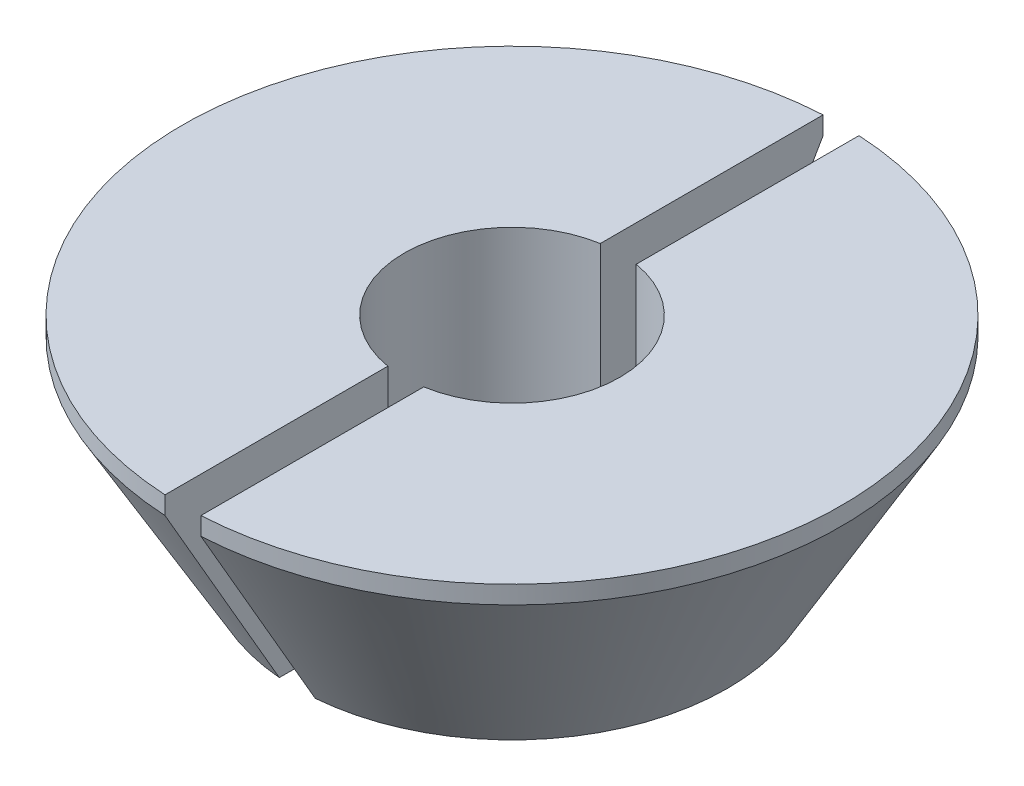
SolidWorks part; units mm, degrees
ref_plane "Front Plane" through (0, 0, 0) normal (0, 0, 1) x (1, 0, 0)
ref_plane "Top Plane" through (0, 0, 0) normal (0, 1, 0) x (1, 0, 0)
ref_plane "Right Plane" through (0, 0, 0) normal (1, 0, 0) x (0, 0, -1)
sketch "Sketch1" plane through (0, 0, 0) normal (0, 0, 1) x (1, 0, 0)
  line L0 (0, 0) -> (3, 0) construction
  line L1 (0, 0) -> (0, 0.0737) construction
  line L2 (0, 0) -> (0, 0.6512) construction
  line L3 (3, 0) -> (4.5877, 2.75)
  line L4 (4.5877, 2.75) -> (4.5877, 3)
  line L5 (4.5877, 3) -> (1.5, 3)
  line L6 (1.5, 3) -> (1.5, 0)
  line L7 (1.5, 0) -> (3, 0)
  dimension "D1" = 0.25
  dimension "D2" = 1.5
  dimension "D3" = 3
  dimension "D4" = 1.5
  dimension "D5" = 60
revolve "Revolve1" add sketch "Sketch1" angle 360 about L2
sketch "Sketch2" plane through (0, 0, 0) normal (0, 0, 1) x (1, 0, 0)
  line L0 (4.5877, 3) -> (-4.5877, 3) construction
  line L1 (0.25, -3) -> (-0.25, -3)
  line L2 (0.25, -3) -> (0.25, 3)
  line L3 (0.25, 3) -> (-0.25, 3)
  line L4 (-0.25, -3) -> (-0.25, 3)
  line L5 (0.25, -3) -> (-0.25, 3) construction
  line L6 (0.25, 3) -> (-0.25, -3) construction
  point P0 (0, 0)
  dimension "D1" = 0.5
extrude "Cut-Extrude1" cut sketch "Sketch2" against normal through all both and the other way through all
